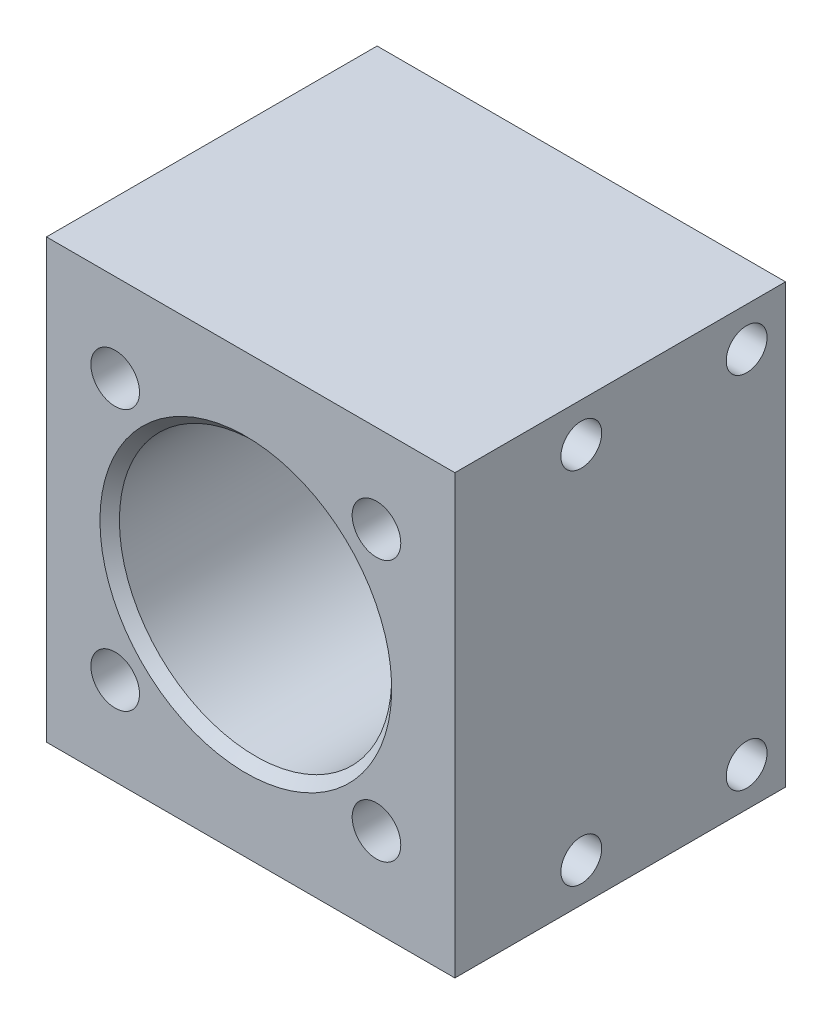
SolidWorks part; units mm, degrees
material "1.0037 (S235JR)"
ref_plane "Płaszczyzna przednia" through (0, 0, 0) normal (0, 0, 1) x (1, 0, 0)
ref_plane "Płaszczyzna górna" through (0, 0, 0) normal (0, 1, 0) x (1, 0, 0)
ref_plane "Płaszczyzna prawa" through (0, 0, 0) normal (1, 0, 0) x (0, 0, -1)
sketch "Szkic1" plane through (0, 0, 0) normal (0, 0, 1) x (1, 0, 0)
  line L0 (42, 22.5) -> (0, 22.5) construction
  line L1 (0, 0) -> (42, 0)
  line L2 (0, 0) -> (0, 45)
  line L3 (0, 45) -> (42, 45)
  line L4 (42, 0) -> (42, 45)
  circle A0 centre (20.5, 22.5) radius 14
  dimension "D3" = 28
  dimension "D1" = 42
  dimension "D2" = 45
  dimension "D4" = 20.5
extrude "Dodanie-wyciągnięcie1" add sketch "Szkic1" along normal blind 34
chamfer "Sfazowanie1" distance 1 angle 45 2 edges at (34.5, 22.5, 0) (34.5, 22.5, 34)
hole_wizard "Otwór gwintowany M6x1.01" positions "Szkic3" profile "Szkic2" tap size "M6x1.0" standard "Ansi Metric"
sketch "Szkic3" plane through (0, 0, 34) normal (0, 0, 1) x (1, 0, 0)
  circle A3 centre (7.065, 9.065) radius 3.3 construction
  circle A4 centre (33.935, 9.065) radius 3.3 construction
  circle A5 centre (33.935, 35.935) radius 3.3 construction
  circle A6 centre (7.065, 35.935) radius 3.3 construction
  point P0 (33.935, 35.935)
  point P2 (7.065, 35.935)
  point P5 (7.065, 9.065)
  point P7 (33.935, 9.065)
sketch "Szkic2" plane through (33.935, 35.935, 34) normal (1, 0, 0) x (0, -1, 0)
  line L0 (0, 0) -> (0, 18.5022)
  line L1 (0, 18.5022) -> (2.5, 17)
  line L2 (2.5, 17) -> (2.5, 0)
  line L5 (2.5, 0) -> (0, 0)
  line L10 (0, 18.5022) -> (-2.5, 17) construction
  line L11 (0, -6.35) -> (0, 107.95) construction
  dimension "Średnica wiertła gwintu" = 5
  dimension "Głębokość otworu gwintowanego" = 17
  dimension "Kąt wiertła" = 118
sketch "Szkic7" plane through (42, 0, 0) normal (1, 0, 0) x (0, 0, -1)
  line L0 (-34, 0) -> (-34, 45) construction
  line L8 (-4, 4) -> (-4, 41)
  line L9 (-4, 41) -> (-30, 41)
  line L10 (-30, 41) -> (-30, 4)
  line L11 (-30, 4) -> (-4, 4)
  line L12 (-4, 4) -> (-4, 41)
  line L13 (-4, 41) -> (-21, 41)
  line L14 (-21, 41) -> (-21, 4)
  line L15 (-21, 4) -> (-4, 4)
  dimension "D2" = 13
  dimension "D1" = 4
hole_wizard "Otwór gwintowany M5x0.82" positions "Szkic9" profile "Szkic8" tap size "M5x0.8" standard "Ansi Metric"
sketch "Szkic9" plane through (42, 0, 0) normal (1, 0, 0) x (0, 0, -1)
  point P0 (-21, 41)
  point P3 (-4, 41)
  point P6 (-4, 4)
  point P9 (-21, 4)
sketch "Szkic8" plane through (42, 41, 21) normal (0, 1, 0) x (0, 0, -1)
  line L0 (0, 0) -> (0, 26.2618)
  line L1 (0, 26.2618) -> (2.1, 25)
  line L2 (2.1, 25) -> (2.1, 0)
  line L5 (2.1, 0) -> (0, 0)
  line L10 (0, 26.2618) -> (-2.1, 25) construction
  line L11 (0, -6.35) -> (0, 107.95) construction
  dimension "Średnica wiertła gwintu" = 4.2
  dimension "Głębokość otworu gwintowanego" = 25
  dimension "Kąt wiertła" = 118
